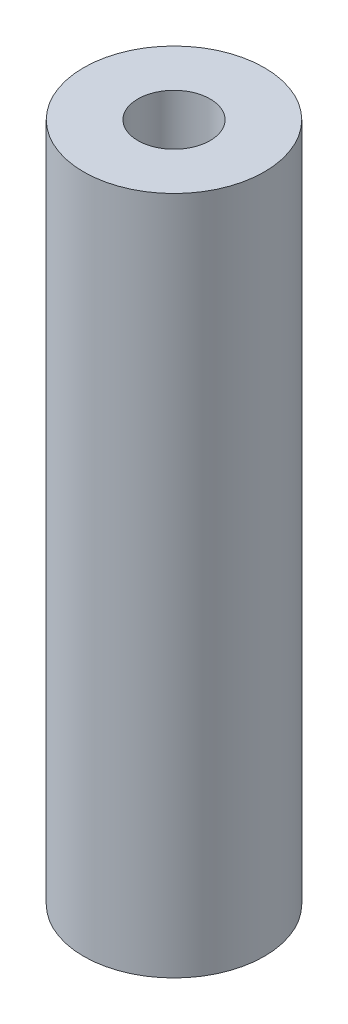
SolidWorks part; units mm, degrees
material "PLA"
ref_plane "前视基准面" through (0, 0, 0) normal (0, 0, 1) x (1, 0, 0)
ref_plane "上视基准面" through (0, 0, 0) normal (0, 1, 0) x (1, 0, 0)
ref_plane "右视基准面" through (0, 0, 0) normal (1, 0, 0) x (0, 0, -1)
sketch "草图1" plane through (0, 0, 0) normal (0, 1, 0) x (1, 0, 0)
  circle A0 centre (0, 0) radius 2.5
  circle A1 centre (0, 0) radius 1
  dimension "D1" = 2
  dimension "D2" = 5
extrude "凸台-拉伸1" add sketch "草图1" along normal blind 18.8
